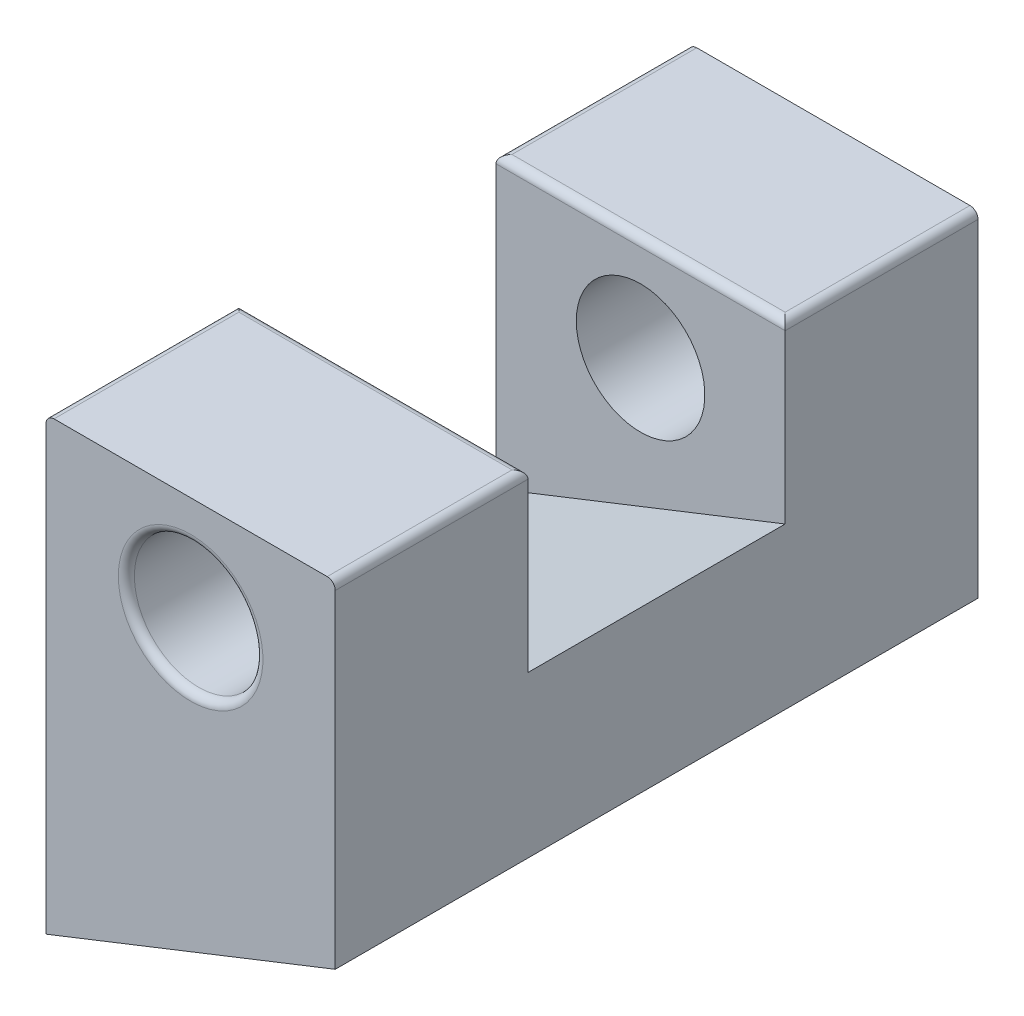
SolidWorks part; units mm, degrees
ref_plane "정면" through (0, 0, 0) normal (0, 0, 1) x (1, 0, 0)
ref_plane "윗면" through (0, 0, 0) normal (0, 1, 0) x (1, 0, 0)
ref_plane "우측면" through (0, 0, 0) normal (1, 0, 0) x (0, 0, -1)
sketch "스케치1" plane through (0, 0, 0) normal (0, 0, 1) x (1, 0, 0)
  line L0 (0, 0) -> (18, 0)
  line L1 (18, 0) -> (18, -20.916)
  line L2 (18, -20.916) -> (0, -28.021)
  line L3 (0, -28.021) -> (0, 0)
  dimension "D1" = 28.021
  dimension "D2" = 20.916
  dimension "D3" = 18
extrude "보스-돌출1" add sketch "스케치1" along normal mid plane 40
sketch "스케치2" plane through (0, 0, 0) normal (0, 0, 1) x (1, 0, 0)
  line L0 (0, -18.021) -> (18, -10.916)
  line L1 (0, 0) -> (0, -28.021) construction
  line L2 (18, -20.916) -> (18, 0) construction
  line L3 (0, -28.021) -> (18, -20.916) construction
  line L4 (0, -18.021) -> (0, 0)
  line L5 (0, 0) -> (18, 0)
  line L6 (18, 0) -> (18, -10.916)
  dimension "D1" = 10
extrude "컷-돌출1" cut sketch "스케치2" against normal mid plane 16
fillet "필렛1" radius 0.5 6 edges at (18, 0, -14) (0, 0, -14) (0, 0, 14) (18, 0, 14) (9, 0, 8) (9, 0, -8)
sketch "스케치5" plane through (0, 0, -8) normal (0, 0, 1) x (1, 0, 0)
  line L0 (18, -2.916) -> (0, -10.021) construction
  line L1 (18, -10.916) -> (18, -0.5) construction
  line L2 (0, -0.5) -> (0, -18.021) construction
  line L3 (0, -18.021) -> (18, -10.916) construction
  circle A0 centre (9, -6.4685) radius 4
  dimension "D2" = 8
  dimension "D1" = 8
extrude "컷-돌출2" cut sketch "스케치5" against normal through all both and the other way through all
fillet "필렛2" radius 0.5 2 edges at (13, -6.4685, -20) (13, -6.4685, 20)
